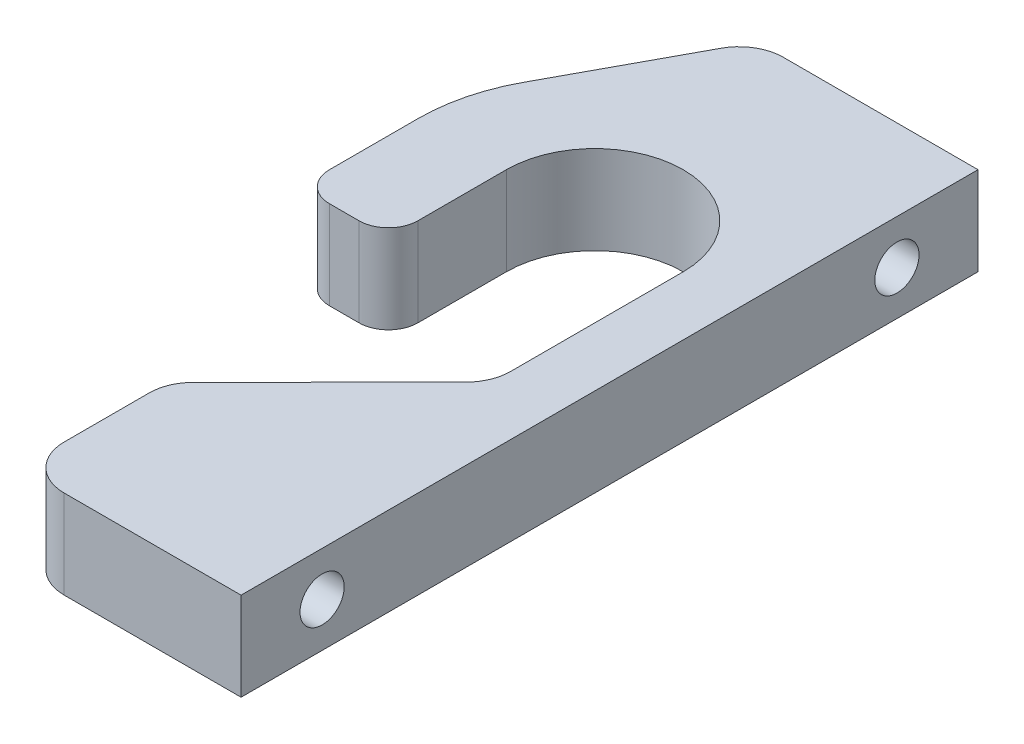
SolidWorks part; units mm, degrees
ref_plane "Front Plane" through (0, 0, 0) normal (0, 0, 1) x (1, 0, 0)
ref_plane "Top Plane" through (0, 0, 0) normal (0, 1, 0) x (1, 0, 0)
ref_plane "Right Plane" through (0, 0, 0) normal (1, 0, 0) x (0, 0, -1)
sketch "Sketch1" plane through (0, 0, 0) normal (0, 1, 0) x (1, 0, 0)
  line L0 (10, 24.6784) -> (10, -8.7313) construction
  line L1 (6, 0) -> (6, -12.9568)
  line L2 (-5, -34) -> (10, -34)
  line L3 (-10.5598, 5.7001) -> (-5, 16)
  line L4 (-5, 16) -> (10, 16)
  line L5 (-12, 0) -> (-12, -8)
  line L6 (-12, -8) -> (-6, -8)
  line L7 (-6, -8) -> (-6, 0)
  line L8 (10, -34) -> (10, 16)
  line L9 (6, -12.9568) -> (-5, -24)
  line L10 (-5, -24) -> (-5, -34)
  arc A0 (6, 0) -> (-6, 0) centre (0, 0) ccw
  arc A1 (-10.5598, 5.7001) -> (-12, 0) centre (0, 0) ccw
  point P1 (0, 0)
  point P5 (8, 30.1303)
  point P18 (8, 30.5397)
  point P19 (1.5443, -22.2656)
  point P20 (6, -12.6353)
  point P21 (1.3621, -22.2429)
  point P22 (15.7875, -34.5112)
  point P23 (-4, -27.7704)
  point P24 (-4, -40.0387)
  point P25 (-4, 19.5503)
  point P26 (-10.1029, 4.3511)
  point P27 (-4, -27.205)
  point P28 (-4, -26.2289)
  point P29 (-4, 20.5733)
  point P30 (-4, -25.6994)
  point P31 (-4, -26.5713)
  dimension "D1" = 6
  dimension "D3" = 6
  dimension "D8" = 10
  dimension "D2" = 8
  dimension "D4" = 15
  dimension "D5" = 12
  dimension "D6" = 4
  dimension "D7" = 10
  dimension "D9" = 50
extrude "Boss-Extrude1" add sketch "Sketch1" along normal mid plane 6
sketch "Sketch2" plane through (10, 0, 0) normal (1, 0, 0) x (0, 0, -1)
  line L0 (-28.5, 0) -> (10.5, 0) construction
  line L1 (-9, 3) -> (-9, 0) construction
  line L2 (-34, 3) -> (16, 3) construction
  line L4 (-34, 3) -> (-34, -3) construction
  circle A0 centre (-28.5, 0) radius 1.5
  circle A1 centre (10.5, 0) radius 1.5
  point P4 (-30.6232, 0)
  point P11 (0, 0)
  point P12 (0, 0)
  dimension "D1" = 4
  dimension "D2" = 3
extrude "Cut-Extrude1" cut sketch "Sketch2" against normal blind 10
fillet "Fillet1" radius 3 4 edges at (-5, 0, 34) (-5, 0, -16) (-5, 0, 24) (6, 0, 12.9568)
fillet "Fillet2" radius 2 2 edges at (-6, 0, 8) (-12, 0, 8)
